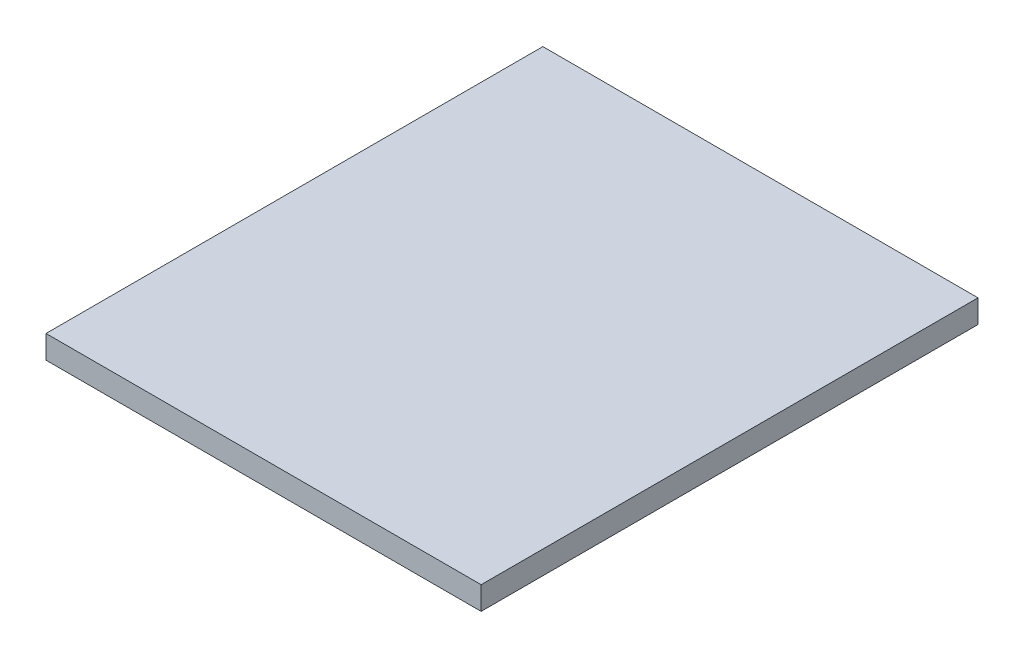
SolidWorks part; units mm, degrees
ref_plane "Front Plane" through (0, 0, 0) normal (0, 0, 1) x (1, 0, 0)
ref_plane "Top Plane" through (0, 0, 0) normal (0, 1, 0) x (1, 0, 0)
ref_plane "Right Plane" through (0, 0, 0) normal (1, 0, 0) x (0, 0, -1)
sketch "Sketch1" plane through (0, 0, 0) normal (0, 1, 0) x (1, 0, 0)
  line L1 (0, 0) -> (28.2, 0)
  line L2 (0, 0) -> (0, 32.2)
  line L3 (0, 32.2) -> (28.2, 32.2)
  line L4 (28.2, 0) -> (28.2, 32.2)
  dimension "D1" = 28.2
  dimension "D2" = 32.2
extrude "Boss-Extrude1" add sketch "Sketch1" along normal blind 1.5
